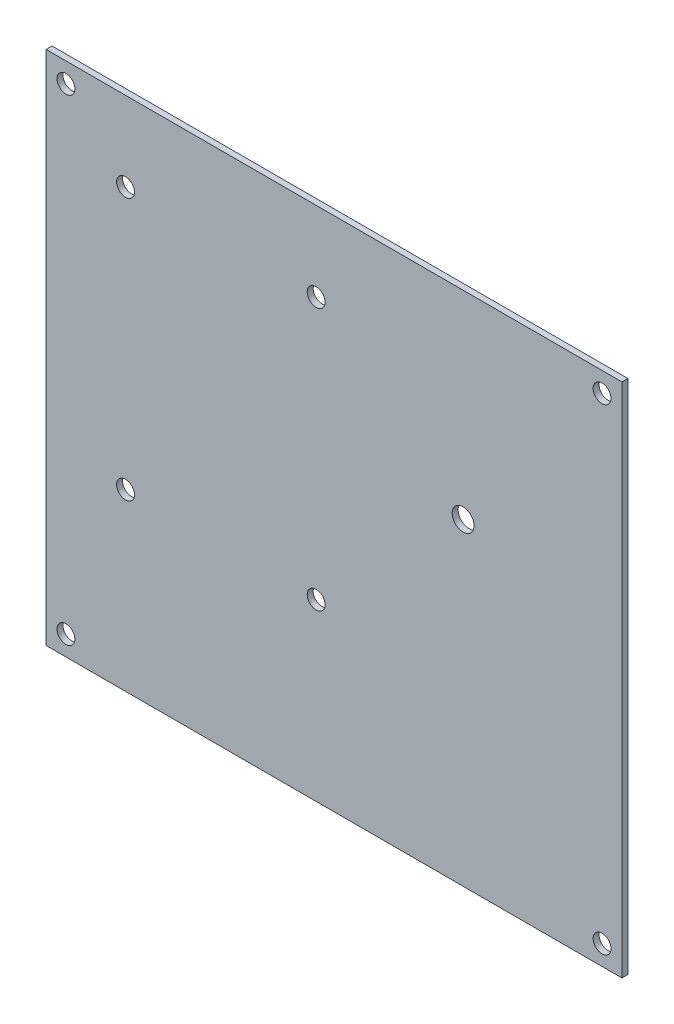
SolidWorks part; units mm, degrees
ref_plane "Спереди" through (0, 0, 0) normal (0, 0, 1) x (1, 0, 0)
ref_plane "Сверху" through (0, 0, 0) normal (0, 1, 0) x (1, 0, 0)
ref_plane "Справа" through (0, 0, 0) normal (1, 0, 0) x (0, 0, -1)
sketch "Эскиз1" plane through (0, 0, 0) normal (0, 0, 1) x (1, 0, 0)
  line L0 (0, 42.3611) -> (0, -41.9385) construction
  line L1 (-56.8336, 0) -> (57.0449, 0) construction
  line L2 (-4.5, -21) -> (-4.5, 45) construction
  line L3 (-72.5, -65) -> (72.5, -65)
  line L4 (-72.5, -65) -> (-72.5, 65)
  line L5 (-72.5, 65) -> (72.5, 65)
  line L6 (72.5, -65) -> (72.5, 65)
  line L7 (-4.5, -21) -> (-52.5, -21) construction
  circle A0 centre (-67.5, 60) radius 2.25
  circle A1 centre (-67.5, -60) radius 2.25
  circle A2 centre (67.5, -60) radius 2.25
  circle A3 centre (67.5, 60) radius 2.25
  circle A4 centre (-52.5, 45) radius 2.25
  circle A5 centre (-52.5, -21) radius 2.25
  circle A6 centre (-4.5, 45) radius 2.25
  circle A7 centre (-4.5, -21) radius 2.25
  circle A8 centre (32.5, 15) radius 2.75
  dimension "D3" = 5
  dimension "D5" = 4.5
  dimension "D8" = 4.5
  dimension "D10" = 66
  dimension "D7" = 20
  dimension "D11" = 66
  dimension "D6" = 48
  dimension "D12" = 50
  dimension "D13" = 48
  dimension "D14" = 40
  dimension "D15" = 5.5
  dimension "D1" = 145
  dimension "D2" = 130
  dimension "D4" = 5
  dimension "D9" = 68
extrude "Вытянуть1" add sketch "Эскиз1" along normal blind 1.5
